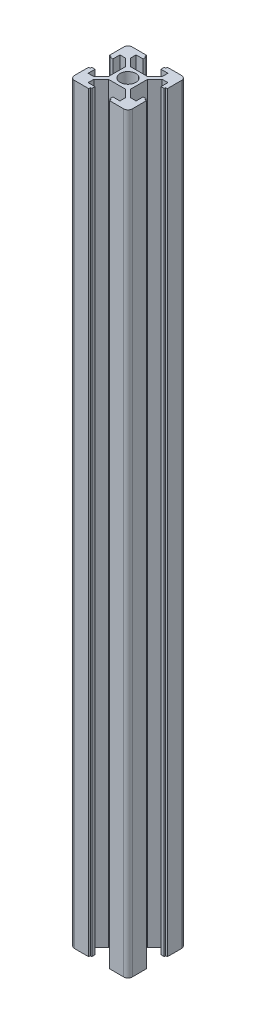
SolidWorks part; units mm, degrees
material "氧化铝"
ref_plane "前视基准面" through (0, 0, 0) normal (0, 0, 1) x (1, 0, 0)
ref_plane "上视基准面" through (0, 0, 0) normal (0, 1, 0) x (1, 0, 0)
ref_plane "右视基准面" through (0, 0, 0) normal (1, 0, 0) x (0, 0, -1)
sketch "草图1" plane through (0, 0, 0) normal (0, 1, 0) x (1, 0, 0)
  line L1 (-10, 10) -> (10, 10)
  line L2 (-10, 10) -> (-10, -10)
  line L3 (-10, -10) -> (10, -10)
  line L4 (10, 10) -> (10, -10)
  line L5 (-10, 10) -> (10, -10) construction
  line L6 (-10, -10) -> (10, 10) construction
  point P0 (0, 0)
  dimension "D1" = 20
  dimension "D2" = 20
extrude "凸台-拉伸1" add sketch "草图1" along normal mid plane 260
sketch "草图4" plane through (0, 130, 0) normal (0, 1, 0) x (1, 0, 0)
  circle A0 centre (0, 0) radius 2.7
  dimension "D1" = 5.4
extrude "切除-拉伸3" cut sketch "草图4" against normal blind 9999
sketch "草图2" plane through (0, 130, 0) normal (0, 1, 0) x (1, 0, 0)
  line L0 (10, 10) -> (-10, 10) construction
  line L1 (-3.6, 10.6) -> (3.6, 10.6)
  line L2 (-3.6, 10.6) -> (-3.6, 9.4)
  line L3 (-3.6, 9.4) -> (3.6, 9.4)
  line L4 (3.6, 10.6) -> (3.6, 9.4)
  line L5 (-3.6, 10.6) -> (3.6, 9.4) construction
  line L6 (-3.6, 9.4) -> (3.6, 10.6) construction
  line L8 (-3.1, 11.7) -> (3.1, 11.7)
  line L9 (-3.1, 11.7) -> (-3.1, 8.3)
  line L10 (-3.1, 8.3) -> (3.1, 8.3)
  line L11 (3.1, 11.7) -> (3.1, 8.3)
  line L12 (-3.1, 11.7) -> (3.1, 8.3) construction
  line L13 (-3.1, 8.3) -> (3.1, 11.7) construction
  point P0 (0, 10)
  point P7 (0, 10)
  dimension "D1" = 1.2
  dimension "D2" = 3.4
  dimension "D3" = 7.2
  dimension "D4" = 6.2
extrude "切除-拉伸1" cut sketch "草图2" against normal blind 9999 contours L2 L3 L4 L1 | L10 L11 L8 L9
sketch "草图3" plane through (0, 130, 0) normal (0, 1, 0) x (1, 0, 0)
  line L5 (5.5, 8.3) -> (-5.5, 8.3)
  line L6 (-3.1, 8.3) -> (3.1, 8.3) construction
  line L7 (-5.5, 8.3) -> (-5.5, 6.3)
  line L8 (-3, 3.8) -> (3, 3.8)
  line L9 (0, 3.8) -> (0, 8.3) construction
  line L12 (-5.5, 6.3) -> (-3, 3.8)
  line L13 (5.5, 6.3) -> (3, 3.8)
  line L14 (5.5, 8.3) -> (5.5, 6.3)
  dimension "D1" = 5.5
  dimension "D2" = 4.5
  dimension "D3" = 2
  dimension "D4" = 3
extrude "切除-拉伸2" cut sketch "草图3" against normal blind 9999
pattern_circular "阵列(圆周)5" count 4 over 360 about axis through (0, 0, 0) along (0, 1, 0) of "切除-拉伸1", "切除-拉伸2"
fillet "圆角1" radius 1.5 4 edges at (-10, 0, 10) (10, 0, 10) (-10, 0, -10) (10, 0, -10)
